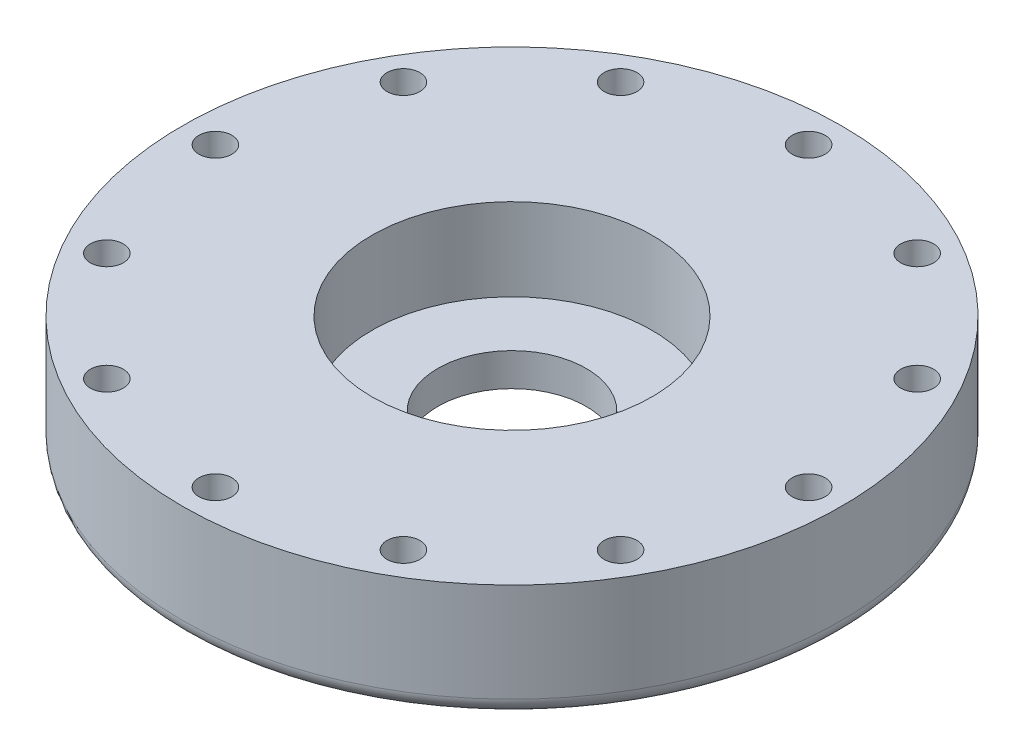
SolidWorks part; units mm, degrees
ref_plane "Front Plane" through (0, 0, 0) normal (0, 0, 1) x (1, 0, 0)
ref_plane "Top Plane" through (0, 0, 0) normal (0, 1, 0) x (1, 0, 0)
ref_plane "Right Plane" through (0, 0, 0) normal (1, 0, 0) x (0, 0, -1)
sketch "Sketch1" plane through (0, 0, 0) normal (0, 1, 0) x (1, 0, 0)
  line L0 (0, 0) -> (-30705.9147, 0) construction
  line L1 (0, 0) -> (0, -30705.9147) construction
  circle A0 centre (0, 0) radius 20
  dimension "D1" = 40
extrude "Boss-Extrude1" add sketch "Sketch1" along normal blind 7
sketch "Sketch2" plane through (0, 7, 0) normal (0, 1, 0) x (1, 0, 0)
  line L0 (0, 0) -> (-50000, 0) construction
  line L1 (0, 0) -> (0, -50000) construction
  circle A0 centre (0, 0) radius 8.5
  dimension "D1" = 17
extrude "Cut-Extrude1" cut sketch "Sketch2" against normal blind 5
sketch "Sketch3" plane through (0, 2, 0) normal (0, 1, 0) x (1, 0, 0)
  line L0 (0, 0) -> (-50000, 0) construction
  line L1 (0, 0) -> (0, -50000) construction
  circle A0 centre (0, 0) radius 4.5
  dimension "D1" = 9
extrude "Cut-Extrude2" cut sketch "Sketch3" against normal through all
sketch "Sketch4" plane through (0, 7, 0) normal (0, 1, 0) x (1, 0, 0)
  line L0 (0, 0) -> (-50000, 0) construction
  line L1 (0, 0) -> (0, -50000) construction
  circle A0 centre (0, 0) radius 18 construction
  circle A1 centre (0, 18) radius 1
  circle A2 centre (9, 15.5885) radius 1
  circle A3 centre (15.5885, 9) radius 1
  circle A4 centre (18, 0) radius 1
  circle A5 centre (15.5885, -9) radius 1
  circle A6 centre (9, -15.5885) radius 1
  circle A7 centre (0, -18) radius 1
  circle A8 centre (-9, -15.5885) radius 1
  circle A9 centre (-15.5885, -9) radius 1
  circle A10 centre (-18, 0) radius 1
  circle A11 centre (-15.5885, 9) radius 1
  circle A12 centre (-9, 15.5885) radius 1
  point P35 (0, 0)
  dimension "D1" = 36
  dimension "D2" = 2
  dimension "D3" = 12
extrude "Cut-Extrude3" cut sketch "Sketch4" against normal blind 5
fillet "Fillet1" radius 1 1 edges at (0, 0, 20)
